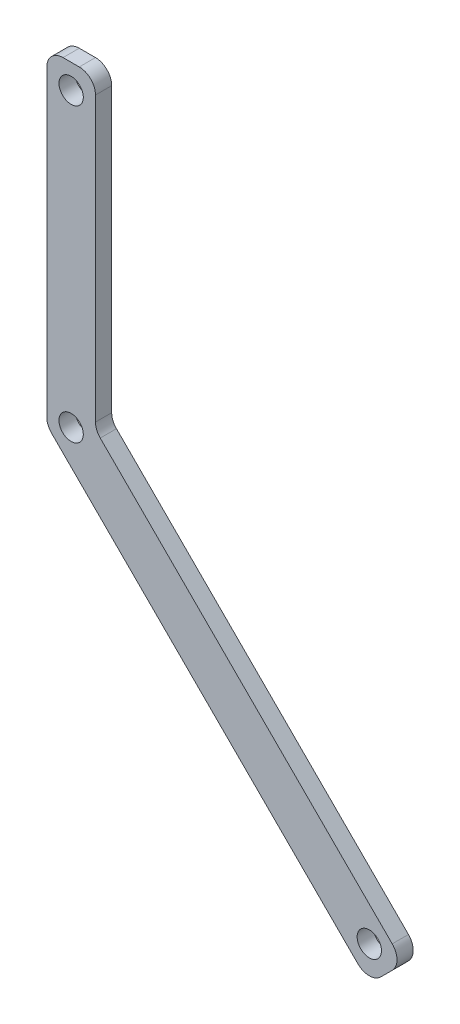
SolidWorks part; units mm, degrees
material "ABS"
ref_plane "Plan de face" through (0, 0, 0) normal (0, 0, 1) x (1, 0, 0)
ref_plane "Plan de dessus" through (0, 0, 0) normal (0, 1, 0) x (1, 0, 0)
ref_plane "Plan de droite" through (0, 0, 0) normal (1, 0, 0) x (0, 0, -1)
sketch "Esquisse2" plane through (0, 0, 0) normal (0, 0, 1) x (1, 0, 0)
  line L0 (0, 0) -> (0, -3.5342) construction
  line L1 (-3, -21) -> (3, -21)
  line L2 (-3, -21) -> (-3, 21)
  line L3 (-3, 21) -> (3, 21)
  line L4 (3, -21) -> (3, 21)
  line L5 (-3, -21) -> (3, 21) construction
  line L6 (-3, 21) -> (3, -21) construction
  line L7 (0, -18) -> (38.8909, -56.8909)
  line L8 (36.7696, -59.0122) -> (41.0122, -54.7696)
  line L9 (41.0122, -54.7696) -> (3, -16.7574)
  line L10 (36.7696, -59.0122) -> (-3, -19.2426)
  circle A0 centre (0, 18) radius 1.5
  circle A1 centre (0, -18) radius 1.5
  circle A2 centre (36.7696, -54.7696) radius 1.5
  point P0 (0, 0)
  point P15 (38.8909, -56.8909)
  dimension "D3" = 3
  dimension "D4" = 0
  dimension "D5" = 3
  dimension "D6" = 3
  dimension "D7" = 3
  dimension "D11" = 3
  dimension "D1" = 36
  dimension "D2" = 6
  dimension "D8" = 135
  dimension "D9" = 55
  dimension "D10" = 6
extrude "Boss.-Extru.3" add sketch "Esquisse2" along normal blind 2
fillet "Congé3" radius 2 6 edges at (36.7696, -59.0122, 1) (41.0122, -54.7696, 1) (-3, -19.2426, 1) (3, -16.7574, 1) (-3, 21, 1) (3, 21, 1)
